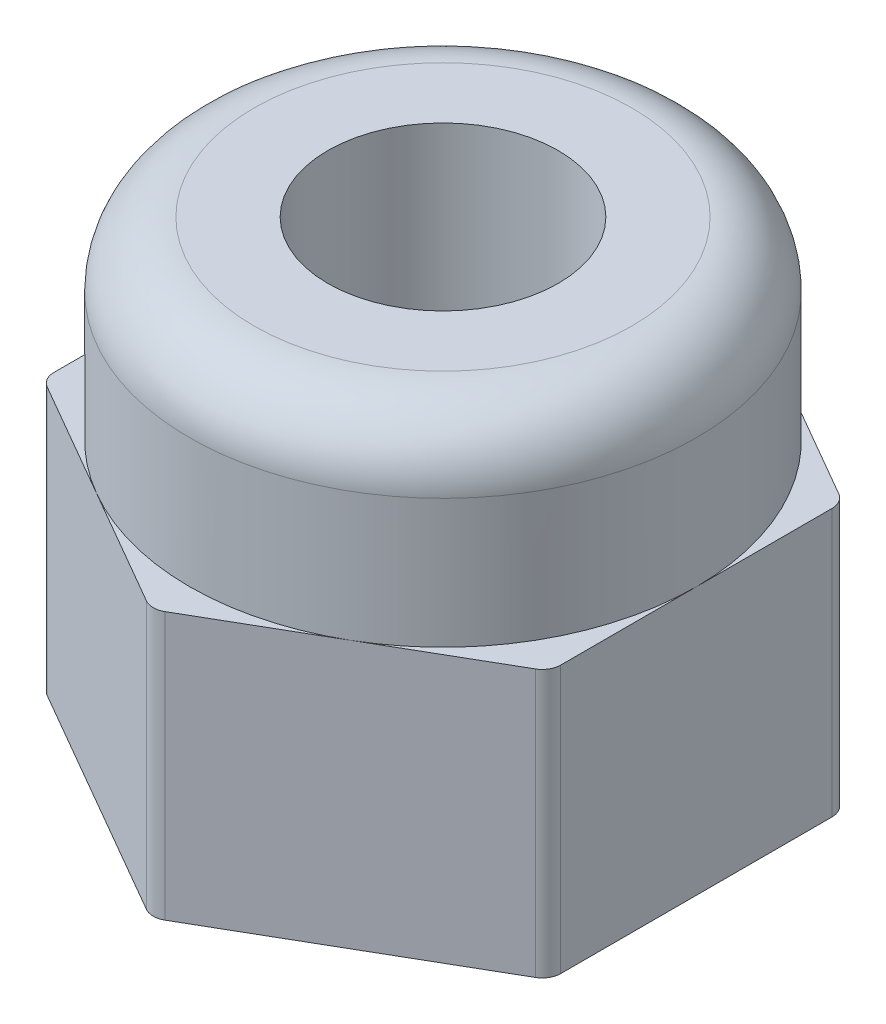
SolidWorks part; units mm, degrees
ref_plane "前视基准面" through (0, 0, 0) normal (0, 0, 1) x (1, 0, 0)
ref_plane "上视基准面" through (0, 0, 0) normal (0, 1, 0) x (1, 0, 0)
ref_plane "右视基准面" through (0, 0, 0) normal (1, 0, 0) x (0, 0, -1)
other "Configuration Table"
sketch "草图1" plane through (0, 0, 0) normal (0, 1, 0) x (1, 0, 0)
  line L1 (2.75, -1.5877) -> (2.75, 1.5877)
  line L2 (2.75, 1.5877) -> (0, 3.1754)
  line L3 (0, 3.1754) -> (-2.75, 1.5877)
  line L4 (-2.75, 1.5877) -> (-2.75, -1.5877)
  line L5 (-2.75, -1.5877) -> (0, -3.1754)
  line L6 (0, -3.1754) -> (2.75, -1.5877)
  circle A0 centre (0, 0) radius 2.75 construction
  dimension "D1" = 5.5
extrude "凸台-拉伸1" add sketch "草图1" along normal blind 2.9
sketch "草图2" plane through (0, 0, 0) normal (0, -1, 0) x (-1, 0, 0)
  circle A0 centre (0, 0) radius 2.75
  dimension "D1" = 5.5
extrude "凸台-拉伸2" add sketch "草图2" against normal blind 5
fillet "圆角2" radius 0.7 1 edges at (0, 5, -2.75)
sketch "草图4" plane through (0, 0, 0) normal (0, -1, 0) x (-1, 0, 0)
  point P0 (0, 0)
hole_wizard "M3 螺纹孔1" positions "草图4" profile "草图5" tap size "M3" standard "GB"
sketch "草图5" plane through (0, 0, 0) normal (1, 0, 0) x (0, 0, -1)
  line L0 (0, 0) -> (0, 10.8511)
  line L1 (0, 10.8511) -> (1.25, 10.1)
  line L2 (1.25, 10.1) -> (1.25, 0)
  line L5 (1.25, 0) -> (0, 0)
  line L10 (0, 10.8511) -> (-1.25, 10.1) construction
  line L11 (0, -6.35) -> (0, 107.95) construction
  dimension "螺纹孔钻头直径" = 2.5
  dimension "螺纹孔钻头深度" = 10.1
  dimension "导头角度" = 118
cosmetic thread "孔螺蚊线1" parameters "D1"=6, "D2"=3
fillet "圆角4" radius 0.2 6 edges at (0, 1.45, 3.1754) (2.75, 1.45, 1.5877) (2.75, 1.45, -1.5877) (0, 1.45, -3.1754) (-2.75, 1.45, -1.5877) (-2.75, 1.45, 1.5877)
